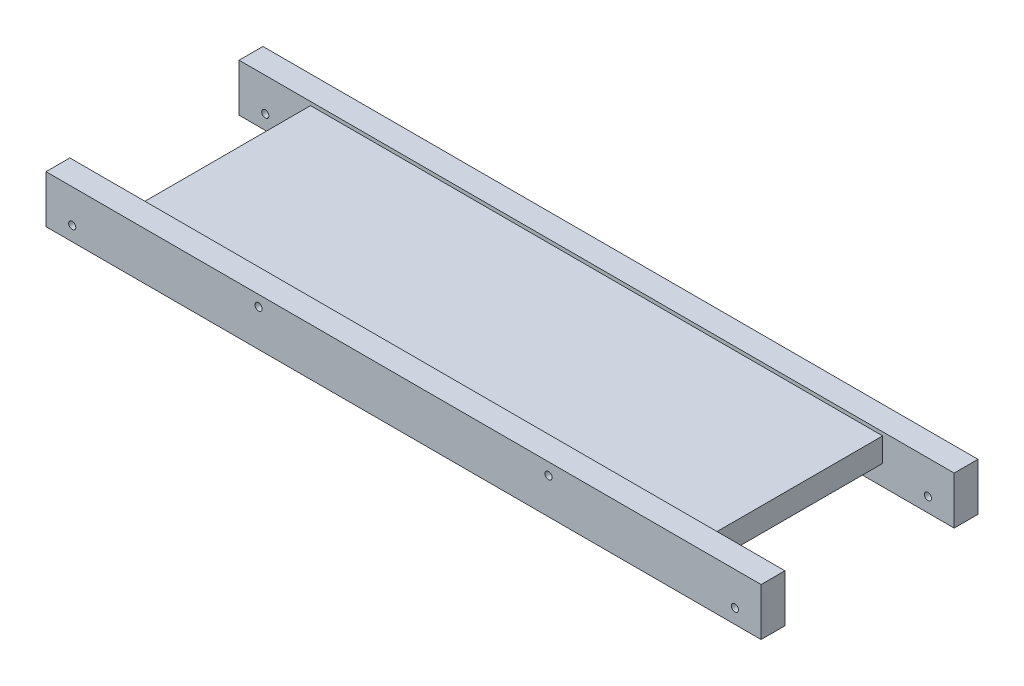
SolidWorks part; units mm, degrees
material "Cedro"
ref_plane "Alzado" through (0, 0, 0) normal (0, 0, 1) x (1, 0, 0)
ref_plane "Planta" through (0, 0, 0) normal (0, 1, 0) x (1, 0, 0)
ref_plane "Vista lateral" through (0, 0, 0) normal (1, 0, 0) x (0, 0, -1)
sketch "Croquis1" plane through (0, 0, 0) normal (0, 0, 1) x (1, 0, 0)
  line L0 (0, 10) -> (0, -10) construction
  line L1 (150, 10) -> (-150, 10)
  line L2 (150, 10) -> (150, -10)
  line L3 (150, -10) -> (-150, -10)
  line L4 (-150, 10) -> (-150, -10)
  line L5 (150, 10) -> (-150, -10) construction
  line L6 (150, -10) -> (-150, 10) construction
  circle A0 centre (-139, -4) radius 1.5
  circle A1 centre (139, -4) radius 1.5
  point P0 (0, 0)
  dimension "D3" = 3
  dimension "D1" = 300
  dimension "D2" = 20
  dimension "D4" = 11
  dimension "D5" = 6
extrude "Saliente-Extruir1" add sketch "Croquis1" against normal blind 10
sketch "Croquis2" plane through (0, 0, 0) normal (0, 0, 1) x (1, 0, 0)
  line L0 (0, -10) -> (0, 10) construction
  line L1 (-150, -10) -> (150, -10) construction
  line L2 (150, 10) -> (-150, 10) construction
  line L3 (-139, 8.5) -> (139, 8.5) construction
  line L5 (-120, 8.5) -> (120, 8.5)
  line L6 (-120, 8.5) -> (-120, -1.5)
  line L7 (-120, -1.5) -> (120, -1.5)
  line L8 (120, 8.5) -> (120, -1.5)
  circle A0 centre (-139, -4) radius 12.5 construction
  circle A1 centre (139, -4) radius 12.5 construction
  dimension "D1" = 25
  dimension "D2" = 10
  dimension "D3" = 240
extrude "Saliente-Extruir2" add sketch "Croquis2" along normal blind 71
sketch "Croquis3" plane through (0, 0, 71) normal (0, 0, 1) x (1, 0, 0)
  line L0 (-28.5982, 4.423) -> (-20.5262, 4.423)
  line L2 (-150, 10) -> (150, 10)
  line L3 (-150, 10) -> (-150, -10)
  line L4 (-150, -10) -> (150, -10)
  line L5 (150, 10) -> (150, -10)
  circle A0 centre (-139, -4) radius 1.5
  circle A1 centre (139, -4) radius 1.5
extrude "Saliente-Extruir3" add sketch "Croquis3" along normal blind 10
sketch "Croquis4" [suppressed] plane through (0, 0, -10) normal (0, 0, -1) x (-1, 0, 0)
  line L0 (0, 10) -> (0, -10) construction
  line L1 (-150, 10) -> (150, 10) construction
  line L2 (150, -10) -> (-150, -10) construction
  line L3 (-60.8276, 5) -> (60.8276, 5)
  circle A0 centre (-60.8276, 5) radius 1.5
  circle A1 centre (60.8276, 5) radius 1.5
  dimension "D3" = 3
  dimension "D1" = 121.6553
  dimension "D2" = 5
extrude "Saliente-Extruir4" [suppressed] add sketch "Croquis4" along normal blind 10
sketch "Croquis5" [suppressed] plane through (0, 0, 81) normal (0, 0, 1) x (1, 0, 0)
  line L0 (0, 10) -> (0, -10) construction
  line L1 (-150, 10) -> (150, 10) construction
  line L2 (-150, -10) -> (150, -10) construction
  line L3 (-60.8276, 5) -> (60.8276, 5)
  circle A0 centre (-60.8276, 5) radius 1.5
  circle A1 centre (60.8276, 5) radius 1.5
  dimension "D3" = 3
  dimension "D1" = 121.6553
  dimension "D2" = 5
extrude "Saliente-Extruir5" [suppressed] add sketch "Croquis5" along normal blind 10
sketch "Croquis6" plane through (0, 0, -10) normal (0, 0, -1) x (-1, 0, 0)
  line L0 (-150, 10) -> (150, 10) construction
  line L1 (0, 0) -> (0, 10) construction
  circle A0 centre (-60.8276, 5) radius 1.5
  circle A1 centre (60.8276, 5.4783) radius 1.5
  dimension "D1" = 3
  dimension "D2" = 5
  dimension "D3" = 121.6553
  dimension "D4" = 60.8276
extrude "Cortar-Extruir1" cut sketch "Croquis6" against normal through all contours A0 | A1
